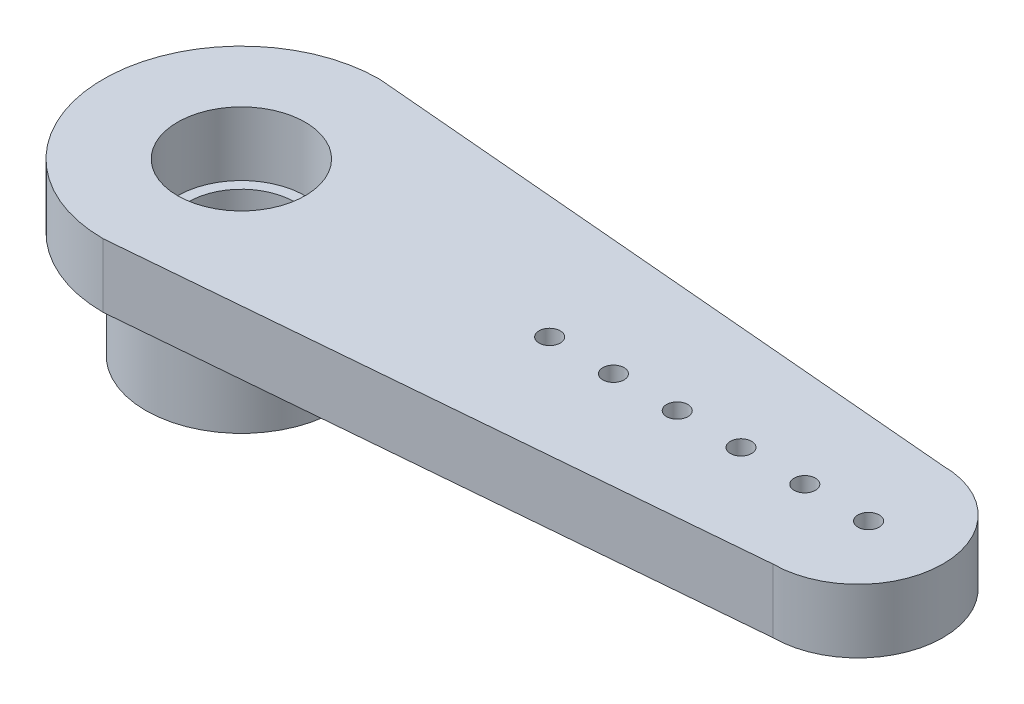
SolidWorks part; units mm, degrees
ref_plane "Front Plane" through (0, 0, 0) normal (0, 0, 1) x (1, 0, 0)
ref_plane "Top Plane" through (0, 0, 0) normal (0, 1, 0) x (1, 0, 0)
ref_plane "Right Plane" through (0, 0, 0) normal (1, 0, 0) x (0, 0, -1)
sketch "Sketch1" plane through (0, 0, 0) normal (0, 1, 0) x (1, 0, 0)
  line L0 (0, 6.5) -> (29, 4)
  line L1 (29, -4) -> (0, -6.5)
  arc A0 (0, 6.5) -> (0, -6.5) centre (0, 0) ccw
  arc A1 (29, -4) -> (29, 4) centre (29, 0) ccw
  circle A2 centre (14.5, 0) radius 0.5
  circle A3 centre (17.5, 0) radius 0.5
  circle A4 centre (20.5, 0) radius 0.5
  circle A5 centre (23.5, 0) radius 0.5
  circle A6 centre (26.5, 0) radius 0.5
  circle A7 centre (29.5, 0) radius 0.5
  dimension "D1" = 13
  dimension "D2" = 8
  dimension "D5" = 1
  dimension "D3" = 29
  dimension "D4" = 14.5
  dimension "D7" = 3
  dimension "D6" = 6
extrude "Boss-Extrude1" add sketch "Sketch1" along normal blind 3
sketch "Sketch3" plane through (0, 0, 0) normal (0, -1, 0) x (1, 0, 0)
  circle A0 centre (0, 0) radius 4.5
  circle A1 centre (0, 0) radius 2.5
  dimension "D1" = 5
  dimension "D2" = 9
extrude "Boss-Extrude2" add sketch "Sketch3" along normal blind 5
sketch "Sketch4" plane through (0, 3, 0) normal (0, 1, 0) x (1, 0, 0)
  circle A0 centre (0, 0) radius 3
  dimension "D1" = 6
extrude "Cut-Extrude1" cut sketch "Sketch4" against normal blind 3
